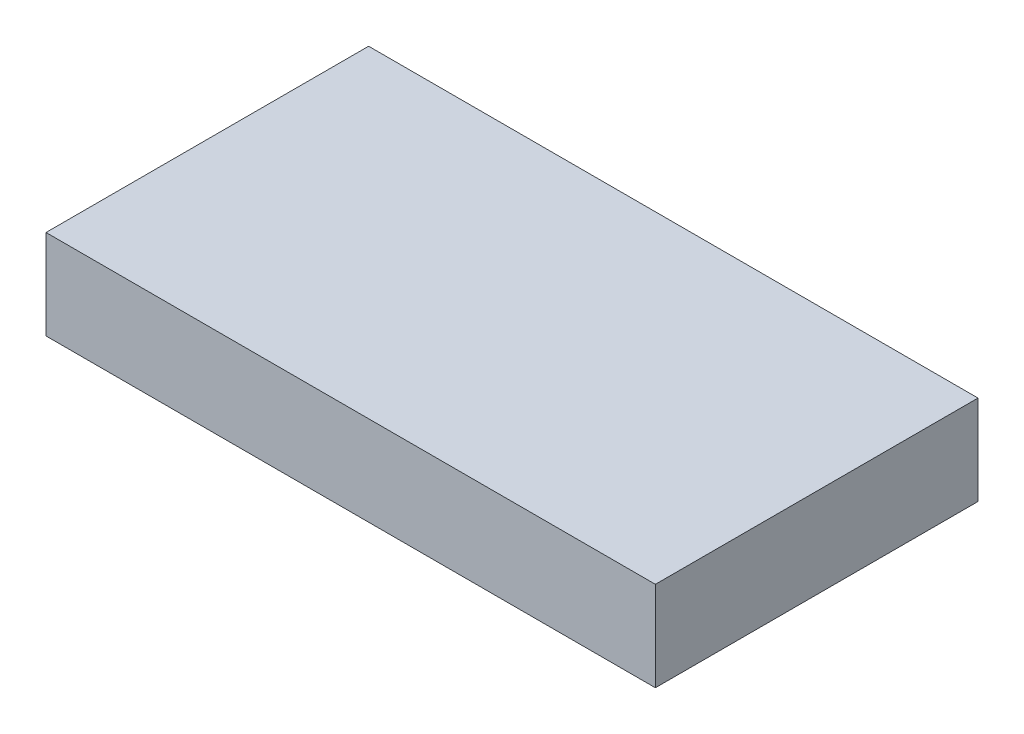
SolidWorks part; units mm, degrees
ref_plane "Front Plane" through (0, 0, 0) normal (0, 0, 1) x (1, 0, 0)
ref_plane "Top Plane" through (0, 0, 0) normal (0, 1, 0) x (1, 0, 0)
ref_plane "Right Plane" through (0, 0, 0) normal (1, 0, 0) x (0, 0, -1)
sketch "Sketch1" plane through (0, 0, 0) normal (0, 1, 0) x (1, 0, 0)
  line L1 (-107.95, -57.15) -> (107.95, -57.15)
  line L2 (-107.95, -57.15) -> (-107.95, 57.15)
  line L3 (-107.95, 57.15) -> (107.95, 57.15)
  line L4 (107.95, -57.15) -> (107.95, 57.15)
  line L5 (-107.95, -57.15) -> (107.95, 57.15) construction
  line L6 (-107.95, 57.15) -> (107.95, -57.15) construction
  point P0 (0, 0)
  dimension "D1" = 215.9
  dimension "D2" = 114.3
extrude "Boss-Extrude1" add sketch "Sketch1" along normal blind 31.75
equation "\"converter-length\"= 8.5in"
equation "\"converter-width\"= 4.5in"
equation "\"converter-height\"= 1.25in"
equation "\"D1@Sketch1\"=\"converter-length\""
equation "\"D2@Sketch1\"=\"converter-width\""
equation "\"D1@Boss-Extrude1\"=\"converter-height\""
